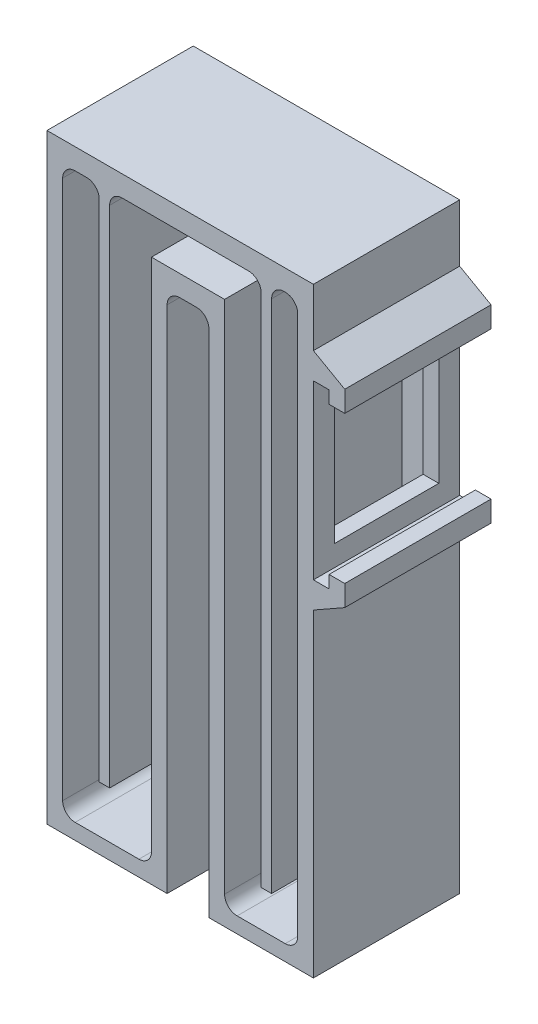
SolidWorks part; units mm, degrees
ref_plane "Front Plane" through (0, 0, 0) normal (0, 0, 1) x (1, 0, 0)
ref_plane "Top Plane" through (0, 0, 0) normal (0, 1, 0) x (1, 0, 0)
ref_plane "Right Plane" through (0, 0, 0) normal (1, 0, 0) x (0, 0, -1)
sketch "Sketch1" plane through (0, 0, 0) normal (0, 0, 1) x (1, 0, 0)
  line L0 (0, 0) -> (0, 97.6)
  line L1 (2.4, 100) -> (5.6, 100)
  line L2 (8, 97.6) -> (8, 0)
  line L3 (-10, 115) -> (18, 115)
  line L4 (18, 108.6) -> (18, 10)
  line L5 (-11, 108.6) -> (-11, 12)
  line L6 (8, 0) -> (28, 0)
  line L7 (28, 0) -> (28, 115)
  line L8 (0, 0) -> (-23, 0)
  line L9 (-23, 0) -> (-23, 115)
  line L10 (18, 115) -> (28, 115)
  line L11 (-23, 115) -> (-10, 115)
  line L12 (-3, 104) -> (11, 104)
  line L13 (11, 104) -> (11, 5.4)
  line L14 (13.4, 3) -> (22.6, 3)
  line L15 (25, 5.4) -> (25, 108.6)
  line L16 (-3, 104) -> (-3, 5.4)
  line L17 (-5.4, 3) -> (-17.6, 3)
  line L18 (-20, 5.4) -> (-20, 108.6)
  line L19 (-17.6, 111) -> (-15.4, 111)
  line L20 (-13, 108.6) -> (-13, 12)
  line L21 (-13, 12) -> (-11, 12)
  line L22 (-8.6, 111) -> (15.6, 111)
  line L23 (18, 10) -> (20, 10)
  line L24 (20, 10) -> (20, 108.6)
  line L25 (22.4, 111) -> (22.6, 111)
  arc A0 (5.6, 100) -> (8, 97.6) centre (5.6, 97.6) cw
  arc A1 (0, 97.6) -> (2.4, 100) centre (2.4, 97.6) cw
  arc A2 (-8.6, 111) -> (-11, 108.6) centre (-8.6, 108.6) ccw
  arc A3 (15.6, 111) -> (18, 108.6) centre (15.6, 108.6) cw
  arc A4 (22.6, 111) -> (25, 108.6) centre (22.6, 108.6) cw
  arc A5 (20, 108.6) -> (22.4, 111) centre (22.4, 108.6) cw
  arc A6 (-15.4, 111) -> (-13, 108.6) centre (-15.4, 108.6) cw
  arc A7 (-20, 108.6) -> (-17.6, 111) centre (-17.6, 108.6) cw
  arc A8 (22.6, 3) -> (25, 5.4) centre (22.6, 5.4) ccw
  arc A9 (11, 5.4) -> (13.4, 3) centre (13.4, 5.4) ccw
  arc A10 (-17.6, 3) -> (-20, 5.4) centre (-17.6, 5.4) cw
  arc A11 (-3, 5.4) -> (-5.4, 3) centre (-5.4, 5.4) cw
  point P8 (4, 115)
  point P11 (4, 100)
  point P44 (8, 100)
  point P47 (0, 100)
  point P52 (18, 111)
  point P59 (-13, 111)
  dimension "D20" = 2.4
  dimension "D1" = 8
  dimension "D2" = 100
  dimension "D3" = 10
  dimension "D4" = 15
  dimension "D5" = 10
  dimension "D6" = 10
  dimension "D7" = 12
  dimension "D8" = 3
  dimension "D9" = 10
  dimension "D10" = 3
  dimension "D11" = 4
  dimension "D12" = 2
  dimension "D13" = 2
  dimension "D14" = 4
  dimension "D15" = 3
  dimension "D16" = 3
  dimension "D17" = 3
  dimension "D18" = 3
  dimension "D19" = 10
extrude "Boss-Extrude1" add sketch "Sketch1" along normal blind 25
sketch "Sketch2" plane through (0, 0, 0) normal (0, 0, 1) x (1, 0, 0)
  line L0 (28, 115) -> (-23, 115) construction
  line L1 (-23, 115) -> (-23, 0) construction
  line L2 (-23, 0) -> (0, 0) construction
  line L3 (0, 0) -> (0, 97.6) construction
  line L4 (2.4, 100) -> (5.6, 100) construction
  line L5 (8, 97.6) -> (8, 0) construction
  line L6 (8, 0) -> (28, 0) construction
  line L7 (28, 0) -> (28, 115) construction
  line L8 (28, 115) -> (-23, 115)
  line L9 (-23, 115) -> (-23, 0)
  line L10 (-23, 0) -> (0, 0)
  line L11 (0, 0) -> (0, 97.6)
  line L12 (2.4, 100) -> (5.6, 100)
  line L13 (8, 97.6) -> (8, 0)
  line L14 (8, 0) -> (28, 0)
  line L15 (28, 0) -> (28, 115)
  arc A0 (2.4, 100) -> (0, 97.6) centre (2.4, 97.6) ccw construction
  arc A1 (8, 97.6) -> (5.6, 100) centre (5.6, 97.6) ccw construction
  arc A2 (2.4, 100) -> (0, 97.6) centre (2.4, 97.6) ccw
  arc A3 (8, 97.6) -> (5.6, 100) centre (5.6, 97.6) ccw
extrude "Boss-Extrude2" add sketch "Sketch2" against normal blind 3
sketch "Sketch3" plane through (28, 0, 0) normal (1, 0, 0) x (0, 0, -1)
  line L0 (-25, 115) -> (3, 115) construction
  line L1 (-21, 95) -> (-1, 95)
  line L2 (-21, 95) -> (-21, 70)
  line L3 (-21, 70) -> (-1, 70)
  line L4 (-1, 95) -> (-1, 70)
  line L5 (3, 0) -> (3, 115) construction
  line L6 (-25, 0) -> (-25, 115) construction
  dimension "D1" = 20
  dimension "D2" = 4
  dimension "D3" = 4
  dimension "D4" = 45
extrude "Cut-Extrude1" cut sketch "Sketch3" against normal up to next
sketch "Sketch4" plane through (0, 0, -3) normal (0, 0, -1) x (-1, 0, 0)
  line L0 (-28, 99) -> (-31, 99)
  line L1 (-28, 0) -> (-28, 115) construction
  line L2 (-31, 99) -> (-31, 96.6)
  line L3 (-31, 96.6) -> (-34, 96.6)
  line L4 (-34, 96.6) -> (-34, 100.6)
  line L5 (-34, 100.6) -> (-28, 104)
  line L6 (-28, 104) -> (-28, 99)
  line L7 (-23.091, 82.5) -> (-42.8553, 82.5) construction
  line L8 (-28, 70) -> (-28, 95) construction
  line L9 (-28, 61) -> (-28, 66)
  line L10 (-34, 64.4) -> (-28, 61)
  line L11 (-34, 68.4) -> (-34, 64.4)
  line L12 (-31, 68.4) -> (-34, 68.4)
  line L13 (-31, 66) -> (-31, 68.4)
  line L14 (-28, 66) -> (-31, 66)
  point P13 (-28, 82.5)
  dimension "D1" = 2.4
  dimension "D2" = 4
  dimension "D3" = 4
  dimension "D4" = 5
  dimension "D5" = 3
  dimension "D6" = 3
extrude "Boss-Extrude3" add sketch "Sketch4" against normal up to surface (28 mm away) up to face at (3.4, 62.6194, 25)
